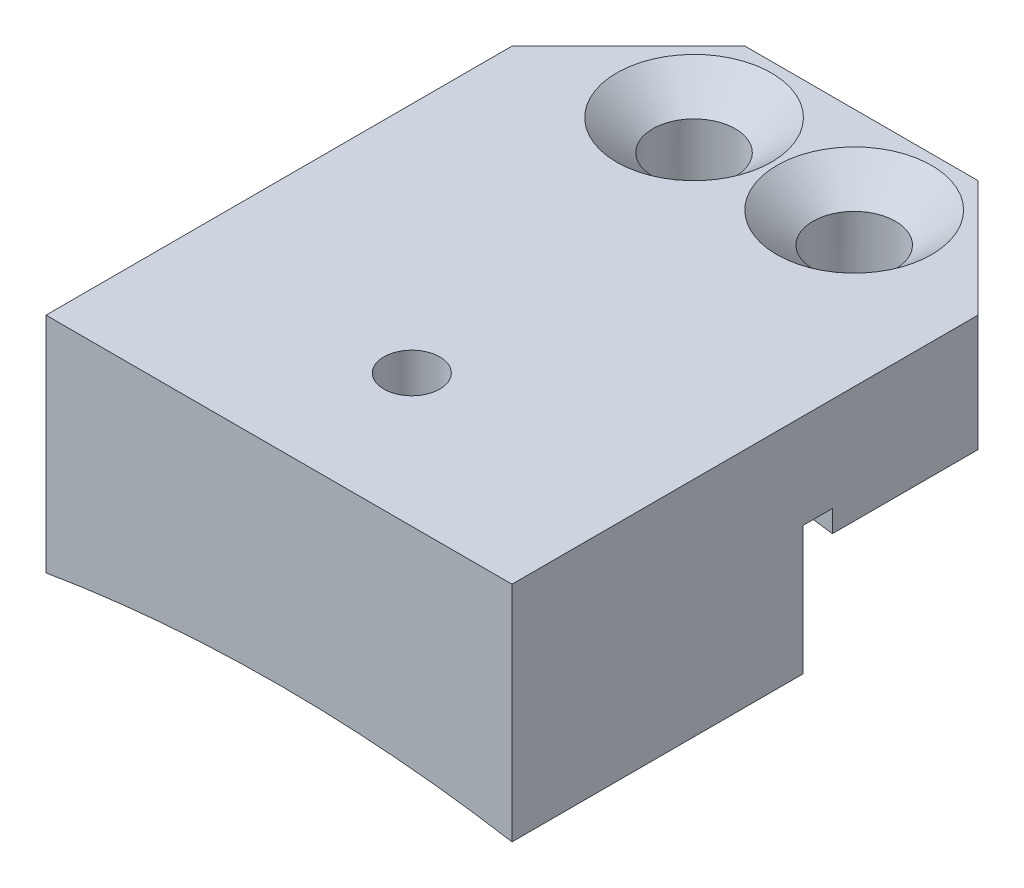
SolidWorks part; units mm, degrees
ref_plane "Front Plane" through (0, 0, 0) normal (0, 0, 1) x (1, 0, 0)
ref_plane "Top Plane" through (0, 0, 0) normal (0, 1, 0) x (1, 0, 0)
ref_plane "Right Plane" through (0, 0, 0) normal (1, 0, 0) x (0, 0, -1)
sketch "Sketch1" plane through (0, 0, 0) normal (0, 1, 0) x (1, 0, 0)
  line L0 (-12.7, 15.875) -> (12.7, -15.875) construction
  line L1 (-12.7, 15.875) -> (12.7, 15.875)
  line L2 (-12.7, 15.875) -> (-12.7, -15.875)
  line L3 (-12.7, -15.875) -> (12.7, -15.875)
  line L4 (12.7, 15.875) -> (12.7, -15.875)
  point P4 (0, 0)
  dimension "D1" = 25.4
  dimension "D2" = 31.75
extrude "Boss-Extrude1" add sketch "Sketch1" along normal blind 6.35
sketch "Sketch2" plane through (0, 0, 15.875) normal (0, 0, 1) x (1, 0, 0)
  line L0 (-12.7, 0) -> (12.7, 0)
  arc A0 (-12.7, 0) -> (12.7, 0) centre (0, -80.9502) cw
  dimension "D1" = 81.9404
extrude "Cut-Extrude1" cut sketch "Sketch2" against normal through all
sketch "Sketch3" plane through (0, 0, 15.875) normal (0, 0, 1) x (1, 0, 0)
  line L0 (-12.7, 6.35) -> (12.7, 6.35)
  line L1 (12.7, 6.35) -> (12.7, -5.816)
  line L2 (-12.7, 6.35) -> (-12.7, -5.816)
  arc A0 (-12.7, -5.816) -> (12.7, -5.816) centre (0, -80.9502) cw
  arc A1 (12.7, 0) -> (-12.7, 0) centre (0, -80.9502) ccw construction
  dimension "D1" = 76.2
extrude "Boss-Extrude2" add sketch "Sketch3" against normal blind 15.875
sketch "Sketch4" plane through (-12.7, 0, 0) normal (-1, 0, 0) x (0, 0, 1)
  line L1 (0, 0) -> (-1.5875, 0)
  line L2 (0, 0) -> (0, 1.1906)
  line L3 (0, 1.1906) -> (-1.5875, 1.1906)
  line L4 (-1.5875, 0) -> (-1.5875, 1.1906)
  dimension "D1" = 1.5875
  dimension "D2" = 1.1906
extrude "Cut-Extrude2" cut sketch "Sketch4" against normal through all
chamfer "Chamfer1" distance 6.35 angle 45 2 edges at (-12.7, 3.175, -15.875) (12.7, 3.175, -15.875)
sketch "Sketch5" plane through (0, 6.35, 0) normal (0, 1, 0) x (1, 0, 0)
  line L0 (-12.7, 9.525) -> (-12.7, -15.875) construction
  line L1 (-12.7, -15.875) -> (12.7, -15.875) construction
  circle A1 centre (0, -8.636) radius 1.524
  dimension "D1" = 3.048
  dimension "D2" = 12.7
  dimension "D3" = 7.239
extrude "Cut-Extrude3" cut sketch "Sketch5" against normal through all
hole_wizard "CSK for #8 Flat Head Machine Screw (100)1" positions "Sketch6" profile "Sketch7" countersink size "#8" standard "ANSI Inch" end condition through all
sketch "Sketch6" plane through (0, 6.35, 0) normal (0, 1, 0) x (1, 0, 0)
  line L0 (0, 15.875) -> (0, 4.8645) construction
  line L1 (6.35, 15.875) -> (-6.35, 15.875) construction
  point P0 (-4.3656, 11.1125)
  point P15 (0, 0)
  point P17 (0, 0)
  point P18 (4.3656, 11.1125)
  dimension "D1" = 4.7625
  dimension "D2" = 4.3656
sketch "Sketch7" plane through (-4.3656, 6.35, -11.1125) normal (1, 0, 0) x (0, 0, 1)
  line L0 (0, 0) -> (0, 12.166)
  line L1 (0, 12.166) -> (2.2479, 12.166)
  line L2 (2.2479, 12.166) -> (2.2479, 1.6518)
  line L3 (2.2479, 1.6518) -> (4.2164, 0)
  line L5 (4.2164, 0) -> (0, 0)
  line L6 (-2.2479, 1.6518) -> (-4.2164, 0) construction
  line L11 (0, -6.35) -> (0, 107.95) construction
  dimension "Thru Hole Dia." = 4.4958
  dimension "Thru Hole Depth" = 12.166
  dimension "Near C'Sink Dia." = 8.4328
  dimension "Near C'Sink Angle" = 100
